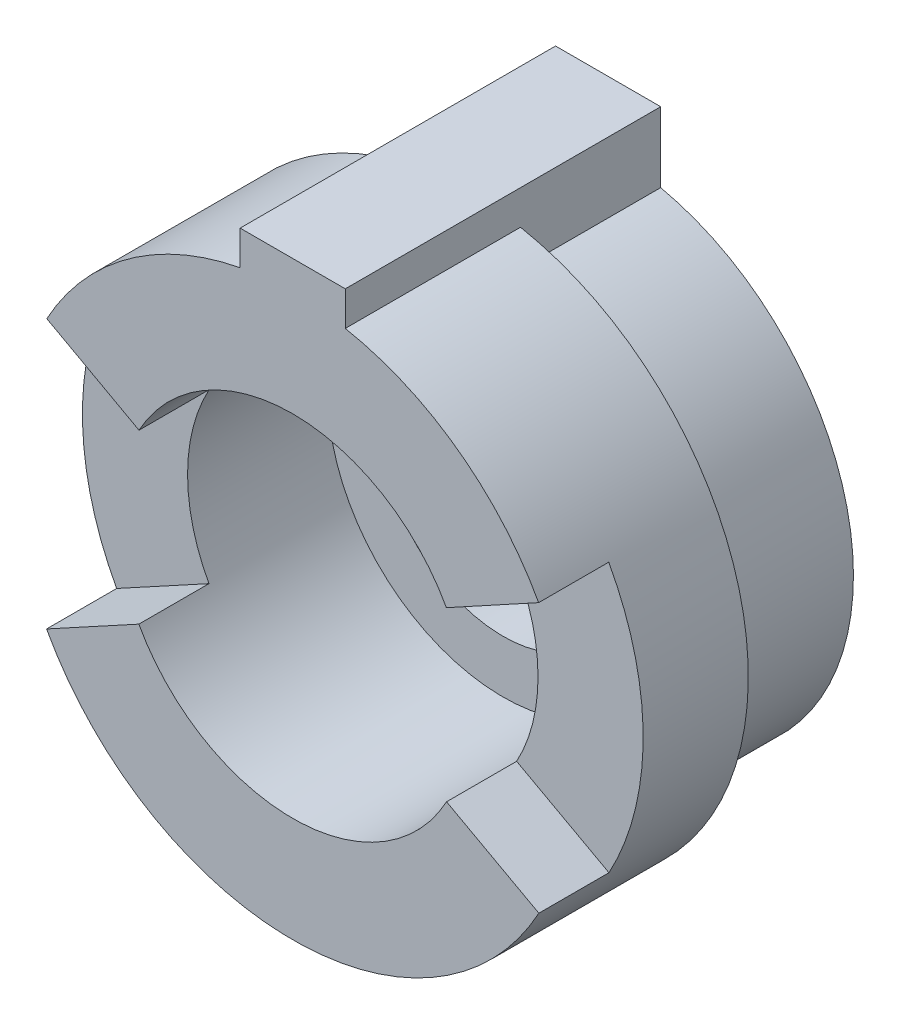
SolidWorks part; units mm, degrees
ref_plane "Front Plane" through (0, 0, 0) normal (0, 0, 1) x (1, 0, 0)
ref_plane "Top Plane" through (0, 0, 0) normal (0, 1, 0) x (1, 0, 0)
ref_plane "Right Plane" through (0, 0, 0) normal (1, 0, 0) x (0, 0, -1)
sketch "Sketch1" plane through (0, 0, 0) normal (0, 0, 1) x (1, 0, 0)
  circle A0 centre (0, 0) radius 8
  circle A1 centre (0, 0) radius 3.5
  dimension "D1" = 7
  dimension "D2" = 16
extrude "Boss-Extrude1" add sketch "Sketch1" along normal blind 3
sketch "Sketch2" plane through (0, 0, 3) normal (0, 0, 1) x (1, 0, 0)
  circle A0 centre (0, 0) radius 8
  circle A1 centre (0, 0) radius 5
  dimension "D1" = 16
  dimension "D2" = 10
extrude "Boss-Extrude2" add sketch "Sketch2" along normal blind 6
sketch "Sketch4" plane through (0, 0, 0) normal (0, 1, 0) x (1, 0, 0)
  line L0 (-8.56, -9) -> (-8.56, -7)
  line L1 (-16.56, -9) -> (-8.56, -9)
  line L2 (8.56, -9) -> (8.56, -7)
  line L3 (8.56, -9) -> (16.56, -9)
  line L4 (-16.56, -9) -> (-16.56, -7)
  line L5 (-16.56, -7) -> (-8.56, -7)
  line L6 (16.56, -9) -> (16.56, -7)
  line L7 (16.56, -7) -> (8.56, -7)
  dimension "D1" = 7
  dimension "D2" = 8.56
  dimension "D3" = 2
  dimension "D4" = 8.56
  dimension "D5" = 8
  dimension "D6" = 8
  dimension "D7" = 2
  dimension "D8" = 7
wrap "Wrap3" sketch "Sketch4" wrap type deboss source sketch "Sketch4" thickness 4 face at (8, 0, 0) parameters "D1"=4
sketch "Sketch5" plane through (0, 0, 0) normal (0, 0, -1) x (-1, 0, 0)
  line L0 (-1.5, 6.8374) -> (-1.5, 7.8581)
  line L2 (1.5, 7.8581) -> (1.5, 6.8374)
  arc A0 (-1.5, 7.8581) -> (1.5, 7.8581) centre (0, 0) ccw
  arc A1 (-1.5, 6.8374) -> (1.5, 6.8374) centre (0, 0) ccw
  dimension "D3" = 7
extrude "Cut-Extrude1" cut sketch "Sketch5" against normal blind 4
sketch "Sketch6" plane through (0, 0, 0) normal (0, 0, -1) x (-1, 0, 0)
  line L0 (-1.5, 7.8581) -> (-1.5, 8.8374)
  line L1 (-1.5, 8.8374) -> (1.5, 8.8374)
  line L2 (1.5, 8.8374) -> (1.5, 7.8581)
  arc A0 (1.5, 7.8581) -> (-1.5, 7.8581) centre (0, 0) ccw
  dimension "D1" = 2
  dimension "D2" = 3
extrude "Boss-Extrude3" add sketch "Sketch6" against normal blind 9
